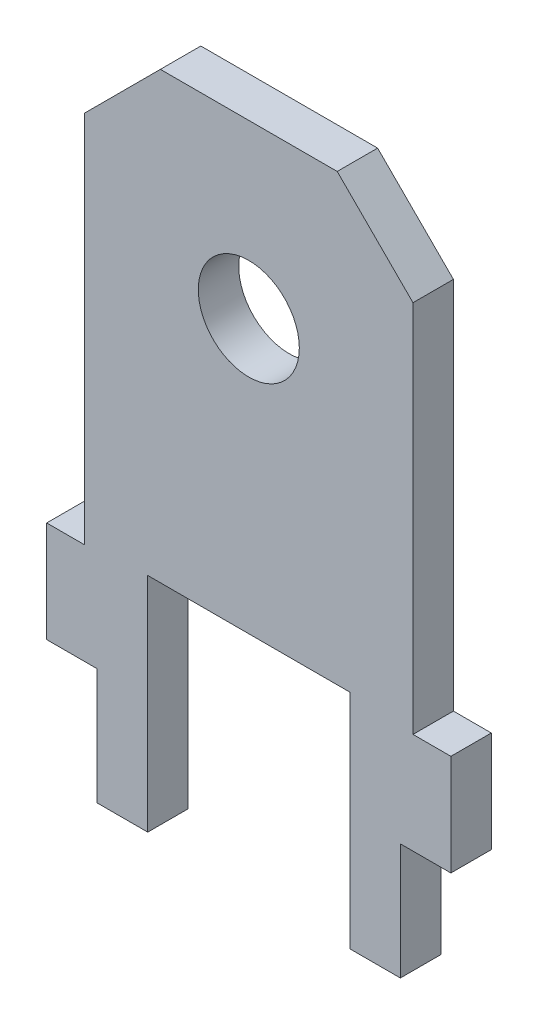
SolidWorks part; units mm, degrees
ref_plane "Спереди" through (0, 0, 0) normal (0, 0, 1) x (1, 0, 0)
ref_plane "Сверху" through (0, 0, 0) normal (0, 1, 0) x (1, 0, 0)
ref_plane "Справа" through (0, 0, 0) normal (1, 0, 0) x (0, 0, -1)
sketch "Эскиз1" plane through (0, 0, 0) normal (0, 0, 1) x (1, 0, 0)
  line L0 (0, 33.3234) -> (0, -28.2976) construction
  line L1 (2, 12.5495) -> (3, 12.5495)
  line L2 (-3, 12.5495) -> (-2, 12.5495)
  line L3 (-3, 12.5495) -> (-3, 14.8495)
  line L4 (-1.75, 25.7495) -> (1.75, 25.7495)
  line L5 (3, 12.5495) -> (3, 14.8495)
  line L6 (3.25, 16.8495) -> (3.25, 24.2495)
  line L7 (-2, 12.5495) -> (-2, 16.9495)
  line L8 (-2, 16.9495) -> (2, 16.9495)
  line L9 (2, 12.5495) -> (2, 16.9495)
  line L10 (3, 14.8495) -> (4, 14.8495)
  line L11 (-4, 14.8495) -> (-4, 16.8495)
  line L12 (3.25, 16.8495) -> (4, 16.8495)
  line L13 (4, 14.8495) -> (4, 16.8495)
  line L14 (-3, 14.8495) -> (-4, 14.8495)
  line L15 (-3.25, 16.8495) -> (-4, 16.8495)
  line L16 (-3.25, 16.8495) -> (-3.25, 24.2495)
  line L17 (-3.25, 24.2495) -> (-1.75, 25.7495)
  line L18 (1.75, 25.7495) -> (3.25, 24.2495)
  circle A0 centre (0, 22.3495) radius 1
  point P4 (3.25, 25.7495)
  point P5 (-3.25, 25.7495)
  dimension "D3" = 2
  dimension "D4" = 3.4
  dimension "D1" = 6.5
  dimension "D2" = 8.8
  dimension "D5" = 4
  dimension "D6" = 10.9
  dimension "D7" = 4
  dimension "D8" = 2
  dimension "D9" = 1
  dimension "D10" = 13.2
  dimension "D13" = 1.5
  dimension "D14" = 1.5
extrude "Вытянуть1" add sketch "Эскиз1" along normal blind 0.8
sketch "Эскиз2" plane through (0, 12.5495, 0) normal (0, -1, 0) x (1, 0, 0)
  line L0 (-4.2971, 0.4) -> (4.2087, 0.4) construction
  line L1 (2.5, 1.5853) -> (2.5, -0.6246) construction
  line L2 (0, 0) -> (0, 1.8211) construction
  line L3 (2, 0.8) -> (2, 0) construction
  line L4 (3, 0.8) -> (3, 0) construction
  line L5 (2, 0.8) -> (3, 0.8) construction
  line L6 (2, 0) -> (3, 0) construction
  circle A0 centre (2.5, 0.4) radius 0.25
  circle A1 centre (-2.5, 0.4) radius 0.25
  dimension "D1" = 0.5
extrude "Вырез-Вытянуть1" cut sketch "Эскиз2" against normal blind 3
